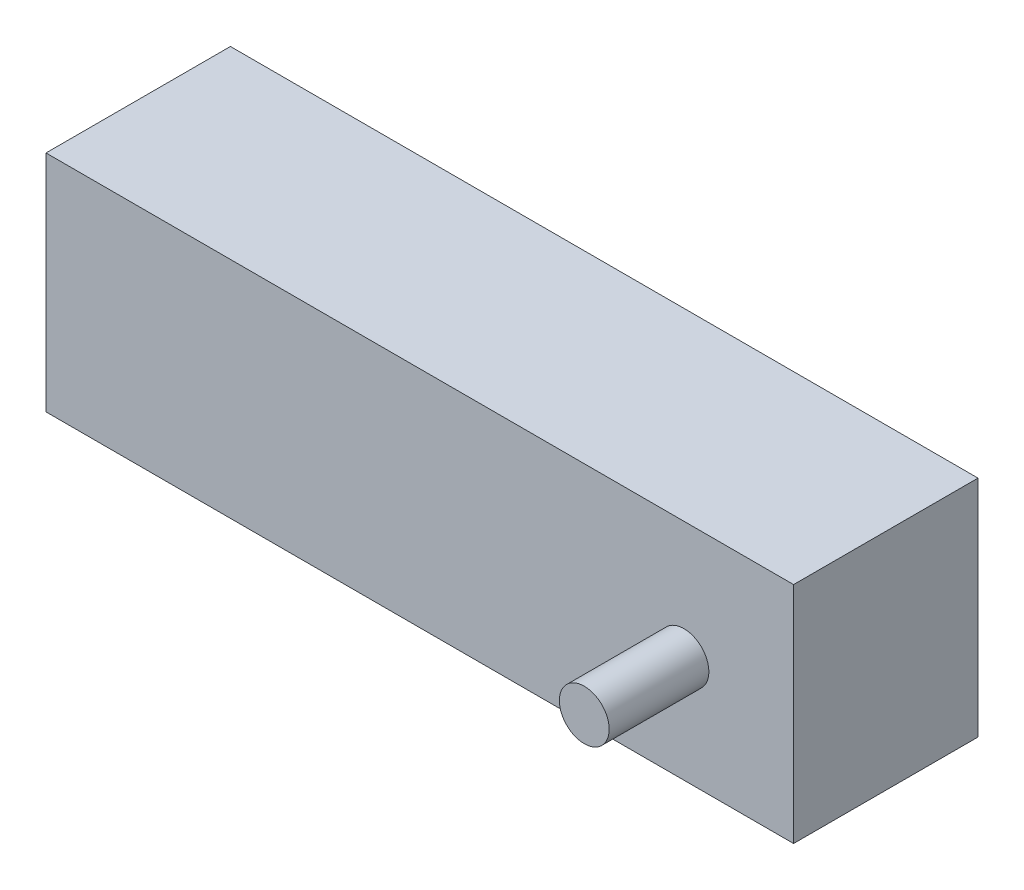
SolidWorks part; units mm, degrees
ref_plane "Front Plane" through (0, 0, 0) normal (0, 0, 1) x (1, 0, 0)
ref_plane "Top Plane" through (0, 0, 0) normal (0, 1, 0) x (1, 0, 0)
ref_plane "Right Plane" through (0, 0, 0) normal (1, 0, 0) x (0, 0, -1)
sketch "Sketch1" plane through (0, 0, 0) normal (0, 0, 1) x (1, 0, 0)
  line L1 (2.5, -13.1095) -> (77.5, -13.1095)
  line L2 (2.5, -13.1095) -> (2.5, 9.3905)
  line L3 (2.5, 9.3905) -> (77.5, 9.3905)
  line L4 (77.5, -13.1095) -> (77.5, 9.3905)
  line L5 (0, -14.3595) -> (0, -9.3595) construction
  line L6 (50, 10.6405) -> (0, 10.6405) construction
  line L7 (50, -14.3595) -> (0, -14.3595) construction
  line L8 (50, 10.6405) -> (0, 10.6405) construction
  dimension "D1" = 75
  dimension "D2" = 2.5
  dimension "D3" = 22.5
  dimension "D4" = 1.25
  dimension "D5" = 1.25
  dimension "D6" = 1.25
extrude "Boss-Extrude1" add sketch "Sketch1" along normal blind 18.5
sketch "Sketch2" plane through (0, 0, 18.5) normal (0, 0, 1) x (1, 0, 0)
  line L0 (77.5, -13.1095) -> (77.5, 9.3905) construction
  circle A0 centre (66.5, -2.4373) radius 2.5
  dimension "D2" = 5
  dimension "D1" = 11
extrude "Boss-Extrude2" add sketch "Sketch2" along normal blind 10
sketch "Sketch3" plane through (0, 0, 0) normal (0, 0, -1) x (-1, 0, 0)
  line L0 (-77.5, -13.1095) -> (-77.5, 9.3905) construction
  line L1 (-77.5, 9.3905) -> (-2.5, 9.3905) construction
  line L2 (-2.5, -13.1095) -> (-77.5, -13.1095) construction
  circle A0 centre (-46, 7.3905) radius 1.5
  circle A1 centre (-46, -11.1095) radius 1.5
  dimension "D2" = 3
  dimension "D4" = 3
  dimension "D1" = 31.5
  dimension "D3" = 2
  dimension "D5" = 2
extrude "Cut-Extrude1" cut sketch "Sketch3" against normal blind 15
